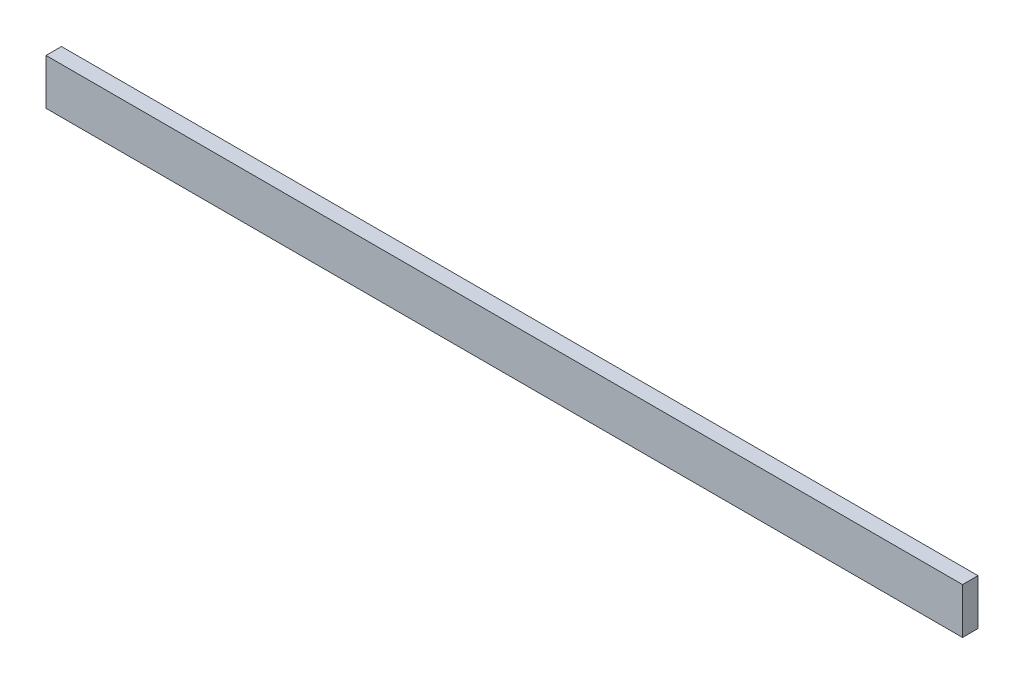
SolidWorks part; units mm, degrees
ref_plane "Plan de face" through (0, 0, 0) normal (0, 0, 1) x (1, 0, 0)
ref_plane "Plan de dessus" through (0, 0, 0) normal (0, 1, 0) x (1, 0, 0)
ref_plane "Plan de droite" through (0, 0, 0) normal (1, 0, 0) x (0, 0, -1)
sketch "Esquisse1" plane through (0, 0, 0) normal (0, 0, 1) x (1, 0, 0)
  line L1 (0, 0) -> (1600, 0)
  line L2 (0, 0) -> (0, 80)
  line L3 (0, 80) -> (1600, 80)
  line L4 (1600, 0) -> (1600, 80)
  dimension "D1" = 1600
  dimension "D2" = 80
extrude "Boss.-Extru.1" add sketch "Esquisse1" along normal blind 27
